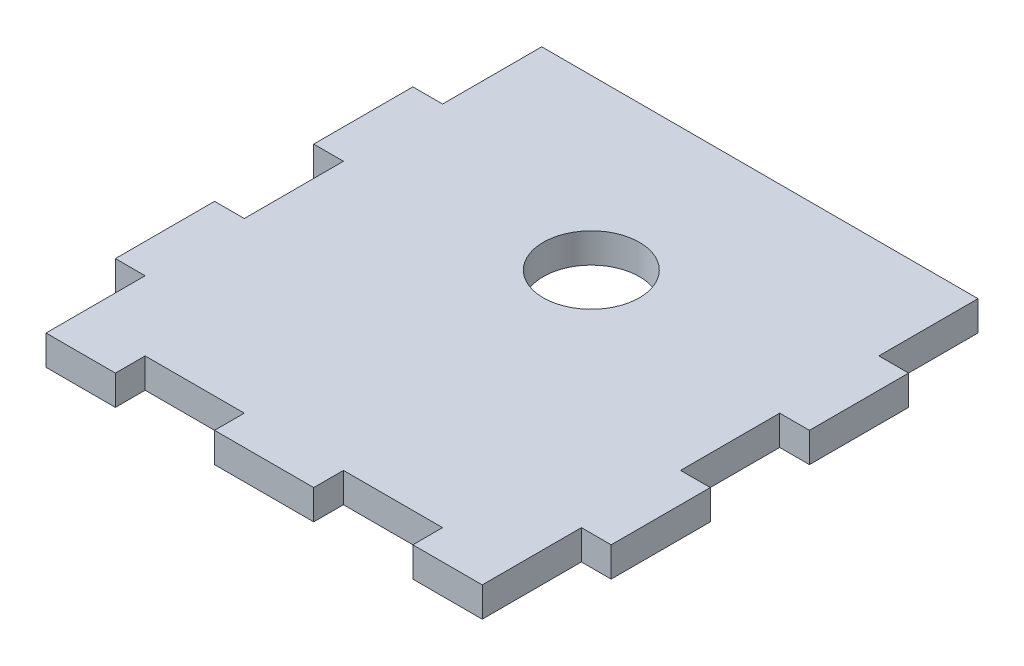
SolidWorks part; units mm, degrees
ref_plane "Alzado" through (0, 0, 0) normal (0, 0, 1) x (1, 0, 0)
ref_plane "Planta" through (0, 0, 0) normal (0, 1, 0) x (1, 0, 0)
ref_plane "Vista lateral" through (0, 0, 0) normal (1, 0, 0) x (0, 0, -1)
sketch "Croquis1" plane through (0, 0, 0) normal (0, 1, 0) x (1, 0, 0)
  line L0 (3, 0) -> (10, 0)
  line L1 (50, 10) -> (50, 20)
  line L2 (47, 50) -> (3, 50)
  line L3 (0, 40) -> (0, 30)
  line L4 (25, 0) -> (20, 0)
  line L5 (20, 0) -> (20, 3)
  line L6 (20, 3) -> (10, 3)
  line L7 (10, 3) -> (10, 0)
  line L8 (50, 30) -> (50, 40)
  line L9 (40, 3) -> (40, 0)
  line L10 (30, 0) -> (30, 3)
  line L11 (30, 3) -> (40, 3)
  line L12 (0, 20) -> (0, 10)
  line L13 (47, 20) -> (47, 30)
  line L14 (47, 30) -> (50, 30)
  line L15 (50, 30) -> (50, 40)
  line L16 (50, 40) -> (47, 40)
  line L17 (47, 40) -> (47, 50)
  line L18 (47, 10) -> (47, 0)
  line L19 (50, 10) -> (47, 10)
  line L20 (47, 20) -> (50, 20)
  line L21 (3, 20) -> (0, 20)
  line L22 (0, 10) -> (3, 10)
  line L23 (3, 10) -> (3, 0)
  line L24 (3, 40) -> (3, 50)
  line L25 (0, 40) -> (3, 40)
  line L26 (3, 30) -> (0, 30)
  line L27 (3, 20) -> (3, 30)
  line L28 (20, 0) -> (30, 0)
  line L29 (40, 0) -> (47, 0)
  circle A0 centre (25, 33) radius 4.85
  dimension "D7" = 9.7
  dimension "D3" = 5
  dimension "D4" = 3
  dimension "D5" = 10
  dimension "D6" = 33
  dimension "D10" = 10
extrude "Saliente-Extruir1" add sketch "Croquis1" along normal blind 3 contours L9 L29 L18 L19 L1 L20 L13 L14 L8 L16 L17 L2 L24 L25 L3 L26 L27 L21 L12 L22 L23 L0 L7 L6 L5 L4 L28 L10 L11 A0
